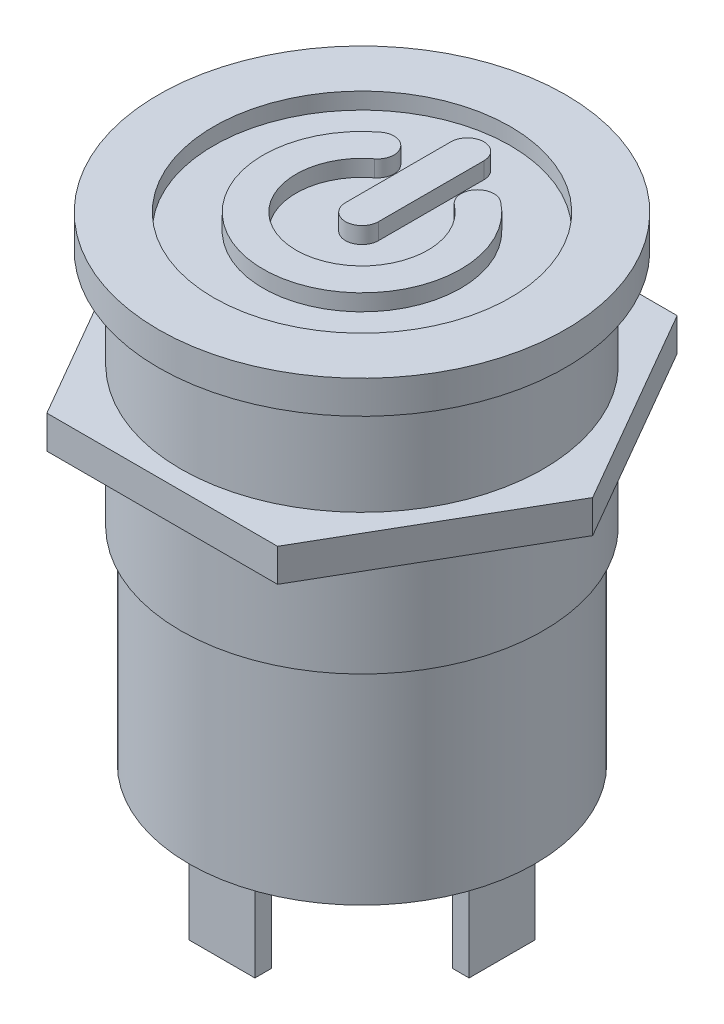
SolidWorks part; units mm, degrees
ref_plane "Plan de face" through (0, 0, 0) normal (0, 0, 1) x (1, 0, 0)
ref_plane "Plan de dessus" through (0, 0, 0) normal (0, 1, 0) x (1, 0, 0)
ref_plane "Plan de droite" through (0, 0, 0) normal (1, 0, 0) x (0, 0, -1)
sketch "Esquisse1" plane through (0, 0, 0) normal (0, 1, 0) x (1, 0, 0)
  circle A0 centre (0, 0) radius 11
  dimension "D1" = 22
extrude "Boss.-Extru.1" add sketch "Esquisse1" against normal blind 14.5
sketch "Esquisse2" plane through (0, 0, 0) normal (0, 1, 0) x (1, 0, 0)
  circle A0 centre (0, 0) radius 12.35
  dimension "D1" = 24.7
extrude "Boss.-Extru.2" add sketch "Esquisse2" along normal blind 2
sketch "Esquisse3" plane through (0, 2, 0) normal (0, 1, 0) x (1, 0, 0)
  line L0 (0, -5) -> (0, 0) construction
  line L1 (0, 0) -> (0, 6.3949) construction
  line L2 (-1, 0) -> (-1, 6.3949)
  line L3 (1, 0) -> (1, 6.3949)
  circle A0 centre (0, 0) radius 9
  arc A1 (-3.0345, 3.9739) -> (3.0345, 3.9739) centre (0, 0) ccw construction
  arc A2 (-3.6414, 4.7687) -> (3.6414, 4.7687) centre (0, 0) ccw
  arc A3 (-2.4276, 3.1791) -> (2.4276, 3.1791) centre (0, 0) ccw
  arc A4 (-2.4276, 3.1791) -> (-3.6414, 4.7687) centre (-3.0345, 3.9739) ccw
  arc A5 (3.6414, 4.7687) -> (2.4276, 3.1791) centre (3.0345, 3.9739) ccw
  arc A6 (-1, 0) -> (1, 0) centre (0, 0) ccw
  arc A7 (1, 6.3949) -> (-1, 6.3949) centre (0, 6.3949) ccw
  point P5 (0, -5)
  point P12 (0, 3.1975)
  dimension "D1" = 18
  dimension "D2" = 5
  dimension "D3" = 1
extrude "Enlèv. mat.-Extru.1" cut sketch "Esquisse3" against normal blind 1
sketch "Esquisse4" plane through (0, -14.5, 0) normal (0, -1, 0) x (1, 0, 0)
  circle A0 centre (0, 0) radius 10.5
  dimension "D1" = 21
extrude "Boss.-Extru.3" add sketch "Esquisse4" along normal blind 12.5
sketch "Esquisse5" plane through (0, -27, 0) normal (0, -1, 0) x (1, 0, 0)
  line L0 (0, 0) -> (0, 1.4764) construction
  line L1 (-8.5, 2) -> (-7.5, 2)
  line L2 (-8.5, 2) -> (-8.5, -2)
  line L3 (-8.5, -2) -> (-7.5, -2)
  line L4 (-7.5, 2) -> (-7.5, -2)
  line L5 (-2, 8.5) -> (2, 8.5)
  line L6 (-2, 8.5) -> (-2, 7.5)
  line L7 (-2, 7.5) -> (2, 7.5)
  line L8 (2, 8.5) -> (2, 7.5)
  line L9 (0, 0) -> (0.9286, 0) construction
  line L10 (2, -8.5) -> (2, -7.5)
  line L11 (-2, -7.5) -> (2, -7.5)
  line L12 (-2, -8.5) -> (-2, -7.5)
  line L13 (-2, -8.5) -> (2, -8.5)
  line L14 (7.5, 2) -> (7.5, -2)
  line L15 (8.5, -2) -> (7.5, -2)
  line L16 (8.5, 2) -> (8.5, -2)
  line L17 (8.5, 2) -> (7.5, 2)
  point P8 (0, 7.5)
  point P10 (-7.5, 0)
  dimension "D1" = 1
  dimension "D2" = 4
  dimension "D3" = 15
  dimension "D4" = 15
extrude "Boss.-Extru.4" add sketch "Esquisse5" along normal blind 6
sketch "Esquisse6" plane through (0, 0, 0) normal (0, -1, 0) x (1, 0, 0)
  line L1 (14, 0) -> (7, 12.1244)
  line L2 (7, 12.1244) -> (-7, 12.1244)
  line L3 (-7, 12.1244) -> (-14, 0)
  line L4 (-14, 0) -> (-7, -12.1244)
  line L5 (-7, -12.1244) -> (7, -12.1244)
  line L6 (7, -12.1244) -> (14, 0)
  circle A0 centre (0, 0) radius 12.1244 construction
  dimension "D1" = 28
extrude "Boss.-Extru.5" add sketch "Esquisse6" along normal blind 2 from offset 6
equation "\"D4@Esquisse5\"=\"D3@Esquisse5\""
